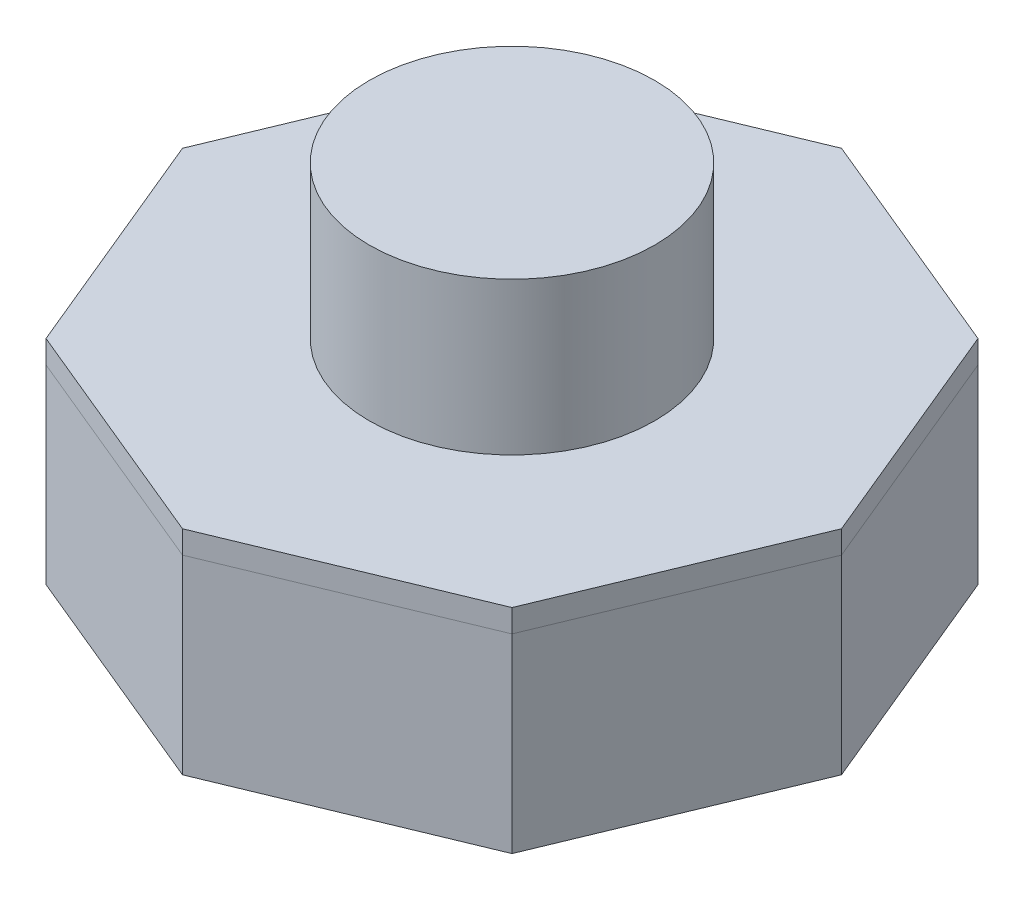
SolidWorks part; units mm, degrees
ref_plane "Front Plane" through (0, 0, 0) normal (0, 0, 1) x (1, 0, 0)
ref_plane "Top Plane" through (0, 0, 0) normal (0, 1, 0) x (1, 0, 0)
ref_plane "Right Plane" through (0, 0, 0) normal (1, 0, 0) x (0, 0, -1)
sketch "Sketch1" plane through (0, 0, 0) normal (0, 1, 0) x (1, 0, 0)
  line L0 (0, -17.3183) -> (12.2459, -12.2459)
  line L1 (17.3183, 0) -> (12.2459, 12.2459)
  line L2 (12.2459, 12.2459) -> (0, 17.3183)
  line L3 (0, 17.3183) -> (-12.2459, 12.2459)
  line L4 (-12.2459, 12.2459) -> (-17.3183, 0)
  line L5 (-17.3183, 0) -> (-12.2459, -12.2459)
  line L6 (-12.2459, -12.2459) -> (0, -17.3183)
  line L7 (12.2459, -12.2459) -> (17.3183, 0)
  circle A0 centre (0, 0) radius 16 construction
extrude "Boss-Extrude1" add sketch "Sketch1" along normal blind 1.2
sketch "Sketch2" plane through (0, 1.2, 0) normal (0, 1, 0) x (1, 0, 0)
  circle A0 centre (0, 0) radius 7.5
extrude "Boss-Extrude2" add sketch "Sketch2" along normal blind 8
sketch "Sketch3" plane through (0, 0, 0) normal (0, -1, 0) x (1, 0, 0)
  line L1 (12.2459, 12.2459) -> (0, 17.3183)
  line L2 (0, 17.3183) -> (-12.2459, 12.2459)
  line L3 (-12.2459, 12.2459) -> (-17.3183, 0)
  line L4 (-17.3183, 0) -> (-12.2459, -12.2459)
  line L5 (-12.2459, -12.2459) -> (0, -17.3183)
  line L6 (0, -17.3183) -> (12.2459, -12.2459)
  line L7 (12.2459, -12.2459) -> (17.3183, 0)
  line L8 (17.3183, 0) -> (12.2459, 12.2459)
  circle A0 centre (0, 0) radius 16 construction
extrude "Boss-Extrude3" add sketch "Sketch3" along normal blind 10 separate body
